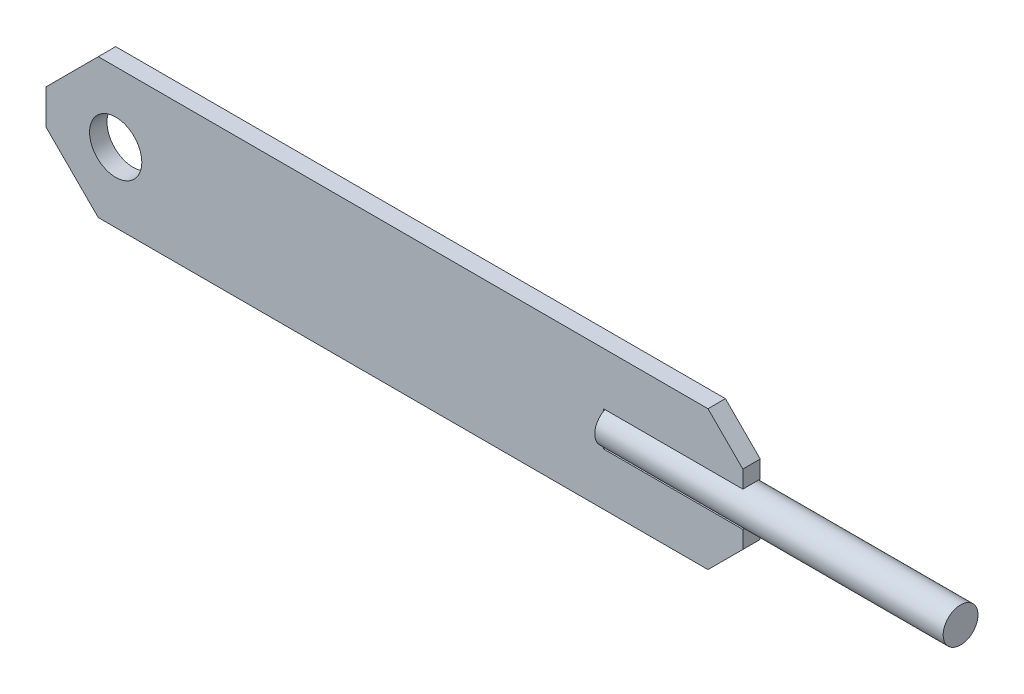
SolidWorks part; units mm, degrees
material "Plain Carbon Steel"
ref_plane "Front Plane" through (0, 0, 0) normal (0, 0, 1) x (1, 0, 0)
ref_plane "Top Plane" through (0, 0, 0) normal (0, 1, 0) x (1, 0, 0)
ref_plane "Right Plane" through (0, 0, 0) normal (1, 0, 0) x (0, 0, -1)
sketch "Sketch1" plane through (0, 0, 0) normal (0, 0, 1) x (1, 0, 0)
  line L0 (0, 0) -> (-160, 0) construction
  line L1 (-200, -40) -> (180, -40)
  line L2 (-200, -40) -> (-200, 40)
  line L3 (-200, 40) -> (180, 40)
  line L4 (200, -20) -> (200, 20)
  line L5 (-200, -40) -> (200, 40) construction
  line L6 (-200, 40) -> (200, -40) construction
  line L7 (180, 40) -> (200, 20)
  line L8 (180, -40) -> (200, -20)
  line L10 (120, -10) -> (280, -10)
  line L11 (120, -10) -> (120, 10)
  line L12 (120, 10) -> (280, 10)
  line L13 (280, -10) -> (280, 10)
  line L14 (120, -10) -> (280, 10) construction
  line L15 (120, 10) -> (280, -10) construction
  circle A0 centre (-160, 0) radius 15
  point P0 (0, 0)
  point P13 (200, 0)
  dimension "D4" = 30
  dimension "D1" = 400
  dimension "D2" = 80
  dimension "D3" = 160
  dimension "D5" = 20
  dimension "D6" = 160
extrude "Boss-Extrude1" add sketch "Sketch1" along normal mid plane 10 contours L11 L12 L4 L7 L3 L2 L1 L8 L10 A0
sketch "Sketch3" plane through (0, 0, 0) normal (1, 0, 0) x (0, 0, -1)
  circle A0 centre (0, 0) radius 10
  dimension "D1" = 20
extrude "Boss-Extrude3" add sketch "Sketch3" along normal blind 200 from vertex at 120 separate body starting at point (120, -10, 5)
chamfer "Chamfer1" distance 30 2 edges at (-200, -40, 0) (-200, 40, 0)
